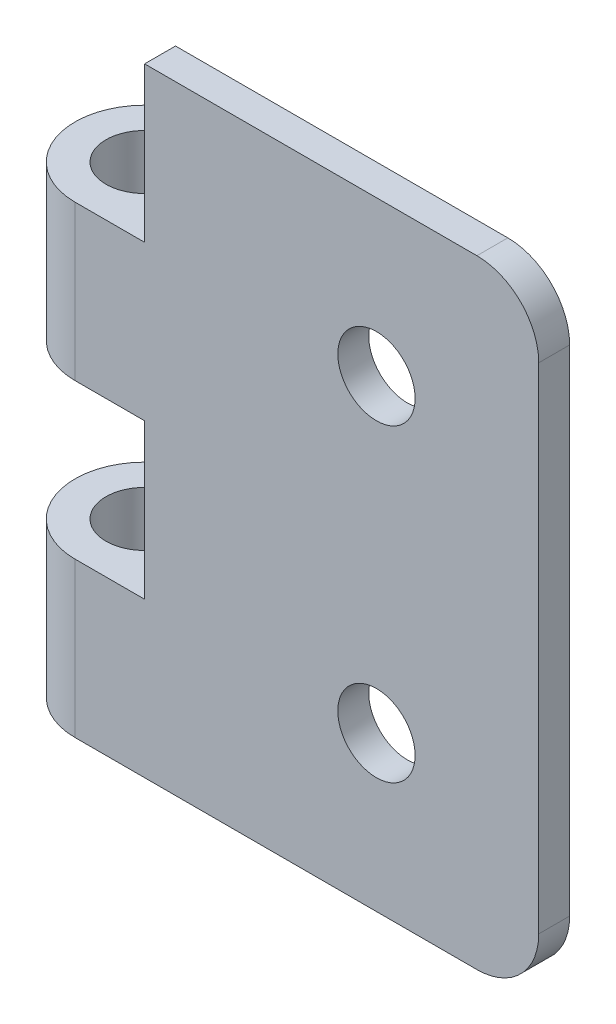
SolidWorks part; units mm, degrees
ref_plane "前视基准面" through (0, 0, 0) normal (0, 0, 1) x (1, 0, 0)
ref_plane "上视基准面" through (0, 0, 0) normal (0, 1, 0) x (1, 0, 0)
ref_plane "右视基准面" through (0, 0, 0) normal (1, 0, 0) x (0, 0, -1)
sketch "草图1" plane through (0, 0, 0) normal (0, 1, 0) x (1, 0, 0)
  line L0 (0, -4.5) -> (30, -4.5)
  line L1 (30, -4.5) -> (30, -2.5)
  line L2 (30, -2.5) -> (3.7417, -2.5)
  circle A0 centre (0, 0) radius 2.5
  arc A1 (3.7417, -2.5) -> (0, -4.5) centre (0, 0) ccw
  dimension "D1" = 9
  dimension "D2" = 5
  dimension "D3" = 2
  dimension "D4" = 30
extrude "凸台-拉伸1" add sketch "草图1" along normal blind 40
sketch "草图2" plane through (0, 0, 4.5) normal (0, 0, 1) x (1, 0, 0)
  line L0 (30, 20) -> (0, 20) construction
  line L1 (30, 40) -> (30, 0) construction
  line L2 (0, 40) -> (0, 0) construction
  circle A0 centre (19.5, 30) radius 2.5
  circle A1 centre (19.5, 10) radius 2.5
  dimension "D1" = 5
  dimension "D2" = 20
  dimension "D3" = 19.5
extrude "切除-拉伸1" cut sketch "草图2" against normal up to next
sketch "草图3" plane through (0, 0, 2.5) normal (0, 0, -1) x (-1, 0, 0)
  line L0 (4.5, 0) -> (4.5, 40) construction
  line L1 (-4.5, 40) -> (4.5, 40)
  line L2 (-4.5, 40) -> (-4.5, 30)
  line L3 (-4.5, 30) -> (4.5, 30)
  line L4 (4.5, 40) -> (4.5, 30)
  line L5 (-4.5, 40) -> (-4.5, 0) construction
  line L6 (-4.5, 20) -> (4.5, 20)
  line L7 (-4.5, 20) -> (-4.5, 10)
  line L8 (-4.5, 10) -> (4.5, 10)
  line L9 (4.5, 20) -> (4.5, 10)
  dimension "D1" = 10
  dimension "D2" = 10
  dimension "D3" = 10
extrude "切除-拉伸2" cut sketch "草图3" against normal mid plane 40
fillet "圆角1" radius 4 2 edges at (30, 40, 3.5) (30, 0, 3.5)
